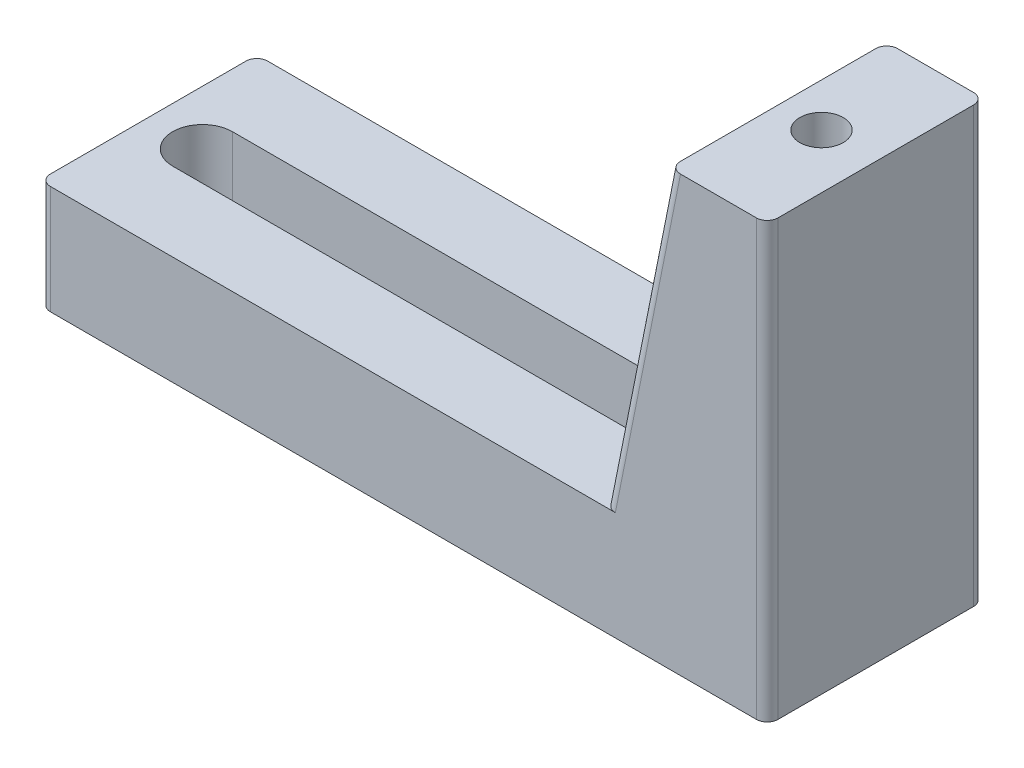
SolidWorks part; units mm, degrees
ref_plane "正面" through (0, 0, 0) normal (0, 0, 1) x (1, 0, 0)
ref_plane "平面" through (0, 0, 0) normal (0, 1, 0) x (1, 0, 0)
ref_plane "右側面" through (0, 0, 0) normal (1, 0, 0) x (0, 0, -1)
sketch "ｽｹｯﾁ1" plane through (0, 0, 0) normal (0, 0, 1) x (1, 0, 0)
  line L0 (0, 0) -> (45, 0)
  line L1 (45, 0) -> (51, 30)
  line L2 (51, 30) -> (60, 30)
  line L3 (60, 30) -> (60, -10)
  line L6 (60, -10) -> (0, -10)
  line L7 (0, -10) -> (0, 0)
  dimension "D1" = 10
  dimension "D2" = 40
  dimension "D3" = 60
  dimension "D4" = 45
  dimension "D5" = 9
extrude "ﾎﾞｽ - 押し出し1" add sketch "ｽｹｯﾁ1" along normal blind 20
sketch "ｽｹｯﾁ2" plane through (0, 30, 0) normal (0, 1, 0) x (1, 0, 0)
  line L0 (0, -10) -> (60, -10) construction
  line L1 (0, -20) -> (0, 0) construction
  line L2 (60, -20) -> (60, 0) construction
  circle A0 centre (55, -10) radius 2
  circle A1 centre (3, -10) radius 2.75
  dimension "D1" = 5.5
  dimension "D4" = 4
  dimension "D2" = 3
  dimension "D3" = 5
extrude "ｶｯﾄ - 押し出し1" cut sketch "ｽｹｯﾁ2" against normal through all
sketch "ｽｹｯﾁ3" plane through (0, -10, 0) normal (0, -1, 0) x (1, 0, 0)
  circle A0 centre (55, 10) radius 2 construction
  circle A1 centre (55, 10) radius 2
extrude "ﾎﾞｽ - 押し出し2" add sketch "ｽｹｯﾁ3" against normal blind 35
sketch "ｽｹｯﾁ4" plane through (0, 0, 0) normal (0, 1, 0) x (1, 0, 0)
  line L0 (45, -20) -> (0, -20) construction
  line L1 (0, 0) -> (-7, 0)
  line L2 (0, 0) -> (0, -20)
  line L3 (0, -20) -> (-7, -20)
  line L4 (-7, 0) -> (-7, -20)
  circle A0 centre (3, -10) radius 2.75 construction
  dimension "D1" = 10
extrude "ﾎﾞｽ - 押し出し3" add sketch "ｽｹｯﾁ4" against normal up to surface (10 mm away) up to face at (3, -10, 12.75)
fillet "ﾌｨﾚｯﾄ2" radius 1 6 edges at (48, 15, 0) (48, 15, 20) (60, 10, 0) (60, 10, 20) (-7, -5, 20) (-7, -5, 0)
sketch "ｽｹｯﾁ5" plane through (0, 0, 0) normal (0, 1, 0) x (1, 0, 0)
  line L0 (-2, -10) -> (40, -10) construction
  line L3 (-2, -7.25) -> (40, -7.25)
  line L4 (-2, -12.75) -> (40, -12.75)
  line L5 (-7, -1) -> (-7, -19) construction
  line L6 (45, -19) -> (45, -1) construction
  arc A2 (-2, -7.25) -> (-2, -12.75) centre (-2, -10) ccw
  arc A3 (40, -12.75) -> (40, -7.25) centre (40, -10) ccw
  point P3 (10.5, -10)
  point P4 (19, -10)
  point P11 (-7, -10)
  dimension "D2" = 5
  dimension "D1" = 5.5
  dimension "D3" = 5
extrude "ｶｯﾄ - 押し出し2" cut sketch "ｽｹｯﾁ5" against normal through all
